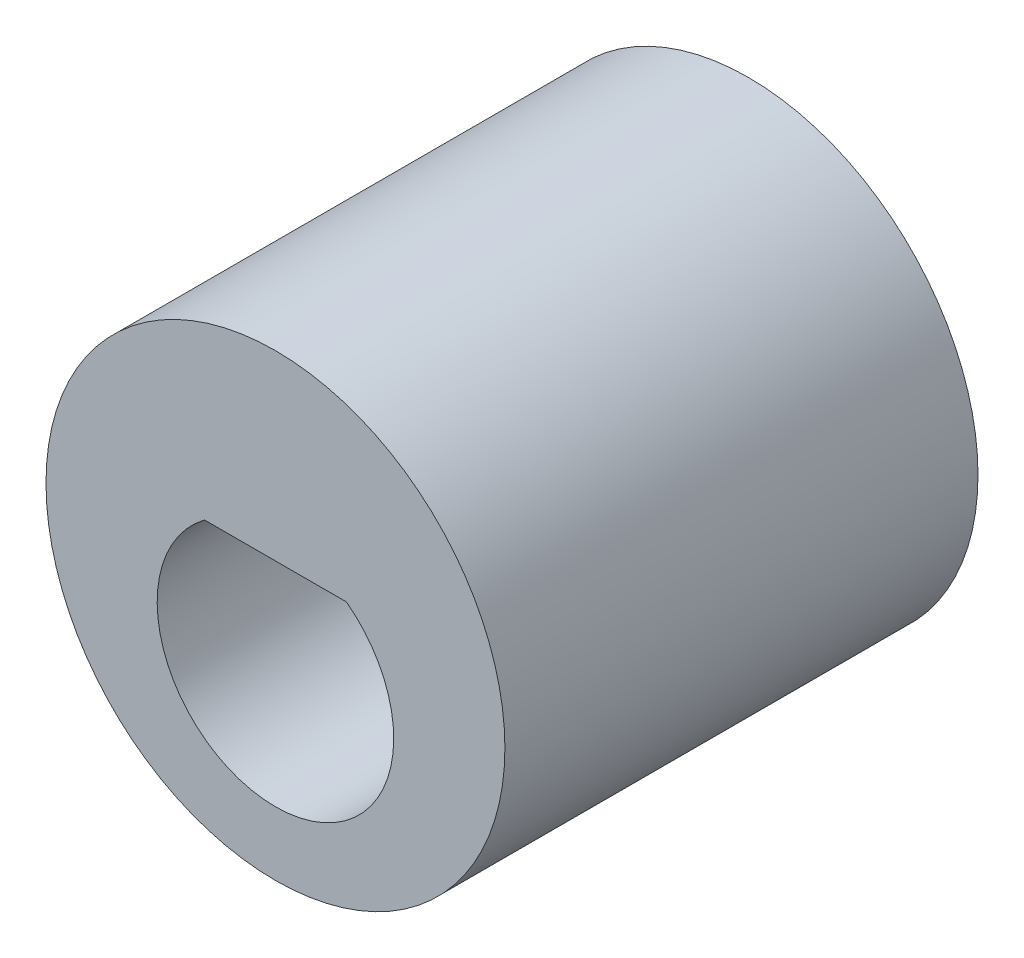
SolidWorks part; units mm, degrees
ref_plane "Plan de face" through (0, 0, 0) normal (0, 0, 1) x (1, 0, 0)
ref_plane "Plan de dessus" through (0, 0, 0) normal (0, 1, 0) x (1, 0, 0)
ref_plane "Plan de droite" through (0, 0, 0) normal (1, 0, 0) x (0, 0, -1)
sketch "Esquisse1" plane through (0, 0, 0) normal (0, 0, 1) x (1, 0, 0)
  line L0 (-1.5, 2) -> (1.5, 2)
  arc A0 (-1.5, 2) -> (1.5, 2) centre (0, 0) ccw
  circle A2 centre (0, 1) radius 4.85
  dimension "D1" = 2.5
  dimension "D2" = 2
  dimension "D4" = 9.7
  dimension "D5" = 1
extrude "Boss.-Extru.1" add sketch "Esquisse1" along normal blind 10
